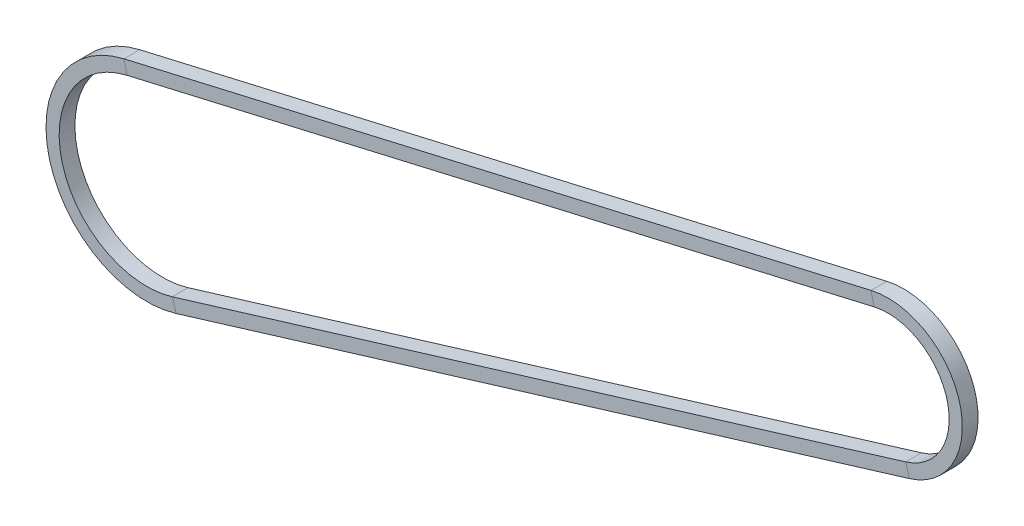
SolidWorks part; units mm, degrees
material "Rubber"
ref_plane "Front Plane" through (0, 0, 0) normal (0, 0, 1) x (1, 0, 0)
ref_plane "Top Plane" through (0, 0, 0) normal (0, 1, 0) x (1, 0, 0)
ref_plane "Right Plane" through (0, 0, 0) normal (1, 0, 0) x (0, 0, -1)
sketch "Sketch2" plane through (0, 0, 0) normal (0, 0, 1) x (1, 0, 0)
  line L0 (0, 0) -> (1, 0) construction
  line L1 (0, 0) -> (0, 1) construction
  line L2 (1.0212, -3.3477) -> (-40.8349, -16.115)
  line L3 (-43.4216, -6.4614) -> (-0.7895, 3.4098)
  arc A0 (-0.7895, 3.4098) -> (1.0212, -3.3477) centre (0, 0) cw
  arc A1 (-40.8349, -16.115) -> (-43.4216, -6.4614) centre (-42.2937, -11.3326) cw
ref_plane "Plane1" through (-43.4216, -6.4614, 0) normal (0.9742, 0.2256, 0) x (0, 0, -1)
sketch "Sketch3" plane through (-43.4216, -6.4614, 0) normal (0.9742, 0.2256, 0) x (0, 0, -1)
  line L1 (-0.45, 0.75) -> (0.45, 0.75)
  line L2 (-0.45, 0.75) -> (-0.45, 0)
  line L3 (-0.45, 0) -> (0.45, 0)
  line L4 (0.45, 0.75) -> (0.45, 0)
  dimension "D1" = 0.9
  dimension "D2" = 0.75
sweep "Sweep1" add profiles "Sketch3" path "Sketch2"
